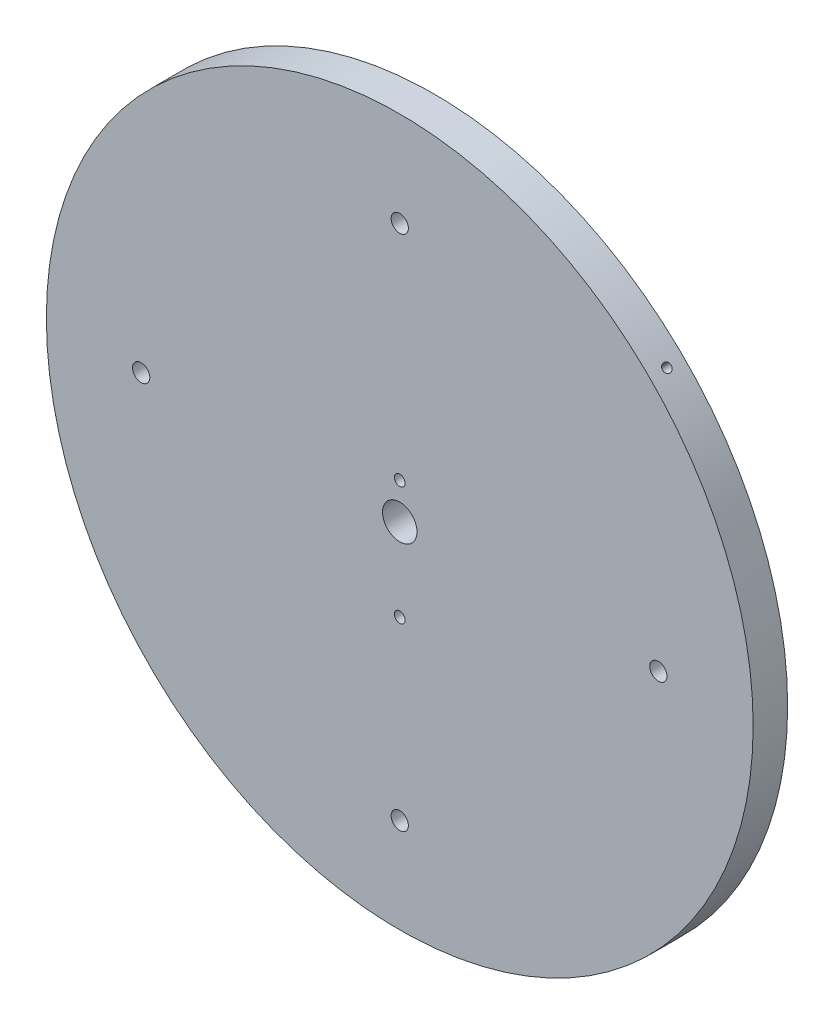
SolidWorks part; units mm, degrees
ref_plane "Front Plane" through (0, 0, 0) normal (0, 0, 1) x (1, 0, 0)
ref_plane "Top Plane" through (0, 0, 0) normal (0, 1, 0) x (1, 0, 0)
ref_plane "Right Plane" through (0, 0, 0) normal (1, 0, 0) x (0, 0, -1)
sketch "Sketch1" plane through (0, 0, 0) normal (0, 0, 1) x (1, 0, 0)
  circle A0 centre (0, 0) radius 82
  dimension "D1" = 164
extrude "Boss-Extrude1" add sketch "Sketch1" along normal blind 8
sketch "Sketch2" plane through (0, 0, 8) normal (0, 0, 1) x (1, 0, 0)
  circle A0 centre (0, 60) radius 2
  dimension "D1" = 4
  dimension "D2" = 60
extrude "Cut-Extrude1" cut sketch "Sketch2" against normal blind 8
pattern_circular "CirPattern1" count 4 every 90 about axis through (0, 0, 0) along (0, 0, 1) of "Cut-Extrude1"
sketch "Sketch3" plane through (0, 0, 8) normal (0, 0, 1) x (1, 0, 0)
  circle A0 centre (0, 0) radius 4
  circle A1 centre (0, 8.38) radius 1.25
  circle A2 centre (0, -19.13) radius 1.25
  dimension "D1" = 8
  dimension "D2" = 2.5
  dimension "D4" = 2.5
  dimension "D3" = 8.38
  dimension "D5" = 19.13
extrude "Cut-Extrude2" cut sketch "Sketch3" against normal blind 10
sketch "Sketch4" plane through (0, 0, 0) normal (0, 0, -1) x (-1, 0, 0)
  line L0 (-162.3225, -20.9619) -> (-166.0133, -22.6084)
  line L1 (-64.0196, 0.4195) -> (-62.3731, -3.2713)
  line L2 (-62.3731, -3.2713) -> (-58.3535, -3.6909)
  line L3 (-58.3535, -3.6909) -> (-55.9804, -0.4195)
  line L4 (-55.9804, -0.4195) -> (-57.6269, 3.2713)
  line L5 (-57.6269, 3.2713) -> (-61.6465, 3.6909)
  line L6 (-61.6465, 3.6909) -> (-64.0196, 0.4195)
  line L7 (-166.0133, -22.6084) -> (-166.4329, -26.628)
  line L8 (-166.4329, -26.628) -> (-163.1615, -29.0011)
  line L9 (-163.1615, -29.0011) -> (-159.4707, -27.3547)
  line L10 (-159.4707, -27.3547) -> (-159.0511, -23.335)
  line L11 (-159.0511, -23.335) -> (-162.3225, -20.9619)
  line L12 (-183.7039, 77.3409) -> (-185.3504, 81.0318)
  line L13 (-185.3504, 81.0318) -> (-189.37, 81.4513)
  line L14 (-189.37, 81.4513) -> (-191.7431, 78.18)
  line L15 (-191.7431, 78.18) -> (-190.0967, 74.4892)
  line L16 (-190.0967, 74.4892) -> (-186.077, 74.0696)
  line L17 (-186.077, 74.0696) -> (-183.7039, 77.3409)
  line L18 (-85.4011, 98.7224) -> (-81.7102, 100.3689)
  line L19 (-81.7102, 100.3689) -> (-81.2907, 104.3885)
  line L20 (-81.2907, 104.3885) -> (-84.562, 106.7616)
  line L21 (-84.562, 106.7616) -> (-88.2528, 105.1151)
  line L22 (-88.2528, 105.1151) -> (-88.6724, 101.0955)
  line L23 (-88.6724, 101.0955) -> (-85.4011, 98.7224)
  circle A0 centre (-60, 0) radius 3.5 construction
  point P30 (-123.8618, 38.8802)
  dimension "D1" = 7
  dimension "D2" = 4
extrude "Cut-Extrude3" cut sketch "Sketch4" against normal blind 3.2
ref_plane "Plane1" through (0, 0, 0) normal (-0.7071, 0.7071, 0) x (0.7071, 0.7071, 0)
ref_plane "Plane2" through (-57.9828, 57.9828, 0) normal (-0.7071, 0.7071, 0) x (0.7071, 0.7071, 0)
sketch "Sketch5" plane through (-57.9828, 57.9828, 0) normal (-0.7071, 0.7071, 0) x (0.7071, 0.7071, 0)
  circle A0 centre (0, -4) radius 1
  dimension "D1" = 2
  dimension "D2" = 4
extrude "Cut-Extrude4" cut sketch "Sketch5" against normal blind 12
pattern_circular "CirPattern2" count 4 every 90 about axis through (0, 0, 0) along (0, 0, 1) of "Cut-Extrude4"
pattern_circular "CirPattern3" count 4 every 90 about axis through (0, 0, 0) along (0, 0, 1) of "Cut-Extrude3"
sketch "Sketch6" plane through (0, 0, 8) normal (0, 0, 1) x (1, 0, 0)
  line L0 (0, 82) -> (0, -82) construction
  circle A0 centre (0, 0) radius 82 construction
